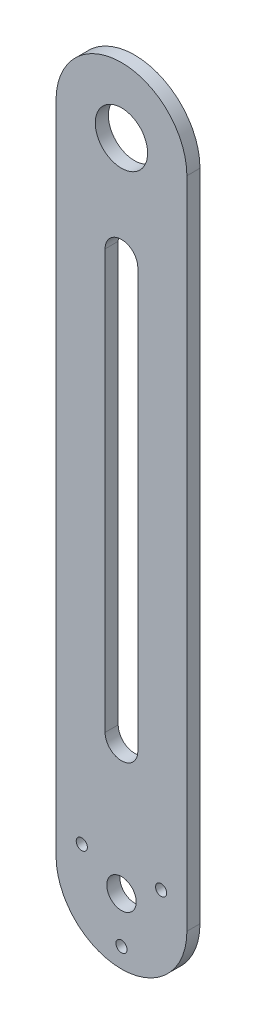
SolidWorks part; units mm, degrees
ref_plane "前视基准面" through (0, 0, 0) normal (0, 0, 1) x (1, 0, 0)
ref_plane "上视基准面" through (0, 0, 0) normal (0, 1, 0) x (1, 0, 0)
ref_plane "右视基准面" through (0, 0, 0) normal (1, 0, 0) x (0, 0, -1)
sketch "草图1" plane through (0, 0, 0) normal (0, 0, 1) x (1, 0, 0)
  line L0 (0, 0) -> (0, -200) construction
  line L3 (-20, 0) -> (-20, -200)
  line L5 (20, -200) -> (20, 0)
  circle A4 centre (0, 0) radius 8
  arc A5 (20, 0) -> (-20, 0) centre (0, 0) ccw
  arc A6 (-20, -200) -> (20, -200) centre (0, -200) ccw
  circle A7 centre (0, -200) radius 4.5
  dimension "D1" = 16
  dimension "D3" = 200
  dimension "D4" = 40
  dimension "D5" = 9
  dimension "D2" = 40
extrude "凸台-拉伸1" add sketch "草图1" along normal blind 4
sketch "草图2" plane through (0, 0, 4) normal (0, 0, 1) x (1, 0, 0)
  line L13 (-5, 0) -> (-5, -200)
  line L14 (5, -200) -> (5, 0)
  line L15 (-5, -31.845) -> (-5, -159.845)
  line L16 (5, -159.845) -> (5, -31.845)
  arc A3 (-5, -31.845) -> (5, -31.845) centre (0, -31.845) cw
  arc A8 (-5, -200) -> (5, -200) centre (0, -200) ccw
  arc A10 (-5, -159.845) -> (5, -159.845) centre (0, -159.845) ccw
  dimension "D1" = 15
extrude "切除-拉伸2" cut sketch "草图2" against normal through all
sketch "草图3" plane through (0, 0, 0) normal (0, 0, -1) x (-1, 0, 0)
  line L0 (0, -200) -> (0, -214) construction
  circle A3 centre (0, -200) radius 14 construction
  circle A4 centre (0, -214) radius 1.7
  circle A5 centre (-12.1244, -193) radius 1.7
  circle A7 centre (12.1244, -193) radius 1.7
  point P15 (0, -200)
  dimension "D2" = 28
  dimension "D3" = 3.4
  dimension "D4" = 3
extrude "切除-拉伸3" cut sketch "草图3" against normal through all
